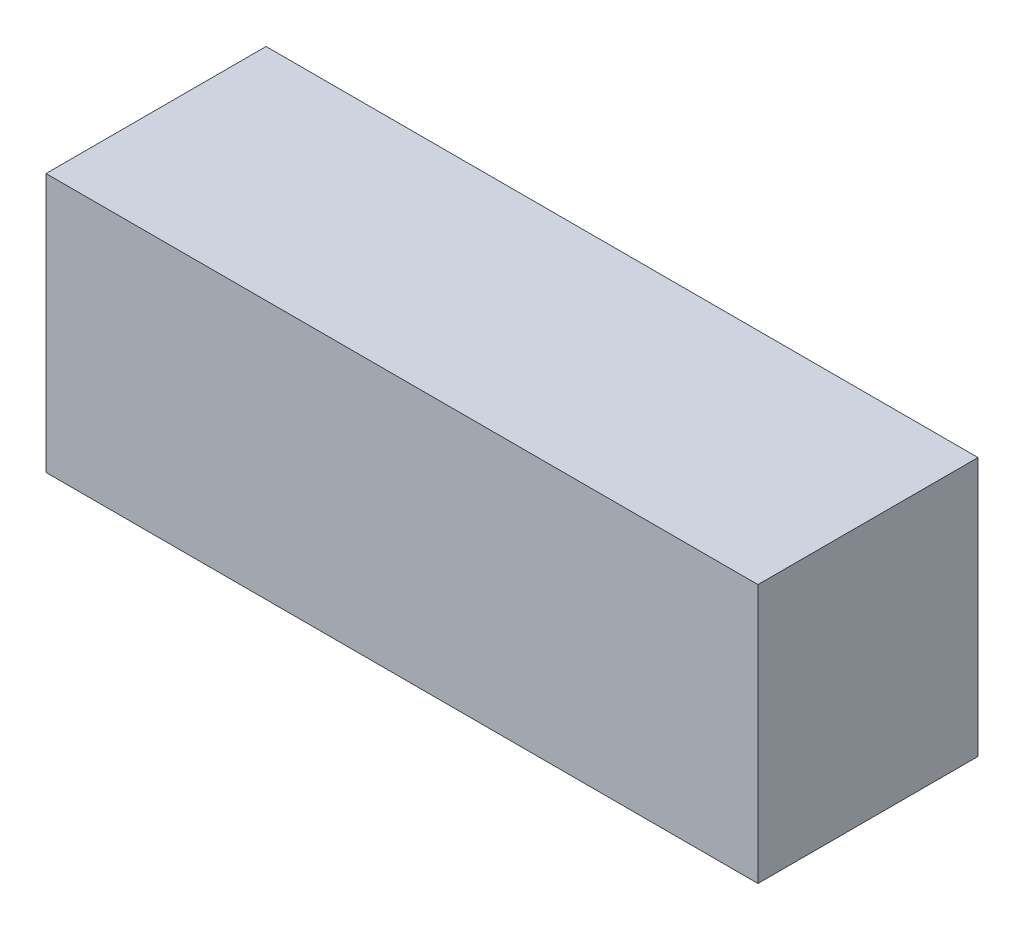
SolidWorks part; units mm, degrees
ref_plane "Front Plane" through (0, 0, 0) normal (0, 0, 1) x (1, 0, 0)
ref_plane "Top Plane" through (0, 0, 0) normal (0, 1, 0) x (1, 0, 0)
ref_plane "Right Plane" through (0, 0, 0) normal (1, 0, 0) x (0, 0, -1)
sketch "Sketch1" plane through (0, 0, 0) normal (0, 1, 0) x (1, 0, 0)
  line L1 (-27.5, -8.5) -> (27.5, -8.5)
  line L2 (-27.5, -8.5) -> (-27.5, 8.5)
  line L3 (-27.5, 8.5) -> (27.5, 8.5)
  line L4 (27.5, -8.5) -> (27.5, 8.5)
  line L5 (-27.5, -8.5) -> (27.5, 8.5) construction
  line L6 (-27.5, 8.5) -> (27.5, -8.5) construction
  point P0 (0, 0)
  dimension "D1" = 55
  dimension "D2" = 17
extrude "Boss-Extrude1" add sketch "Sketch1" along normal blind 20
